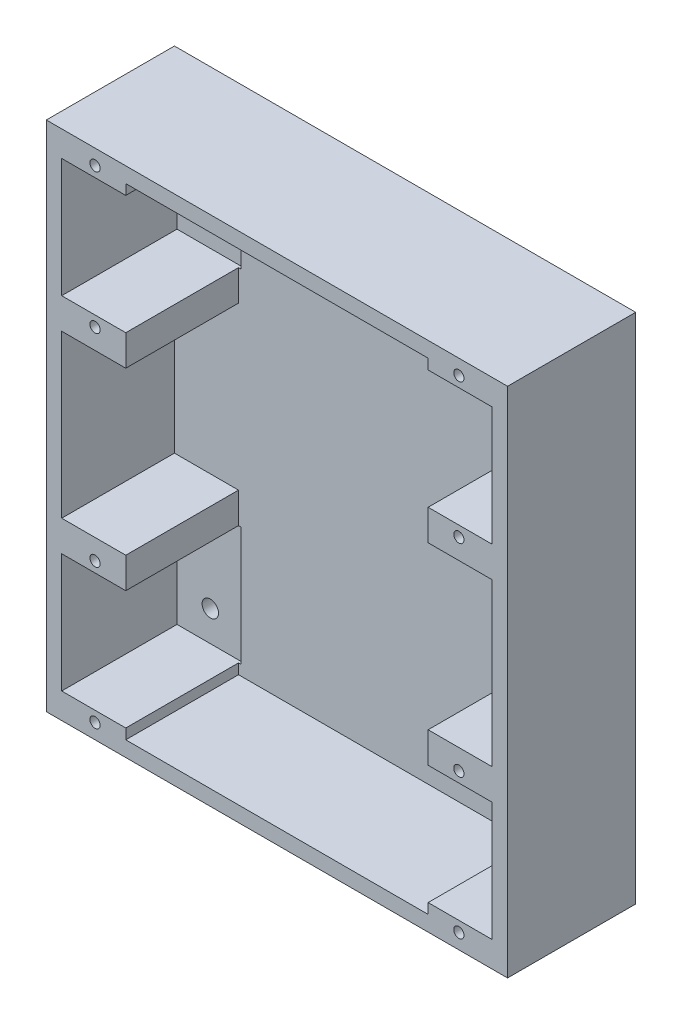
SolidWorks part; units mm, degrees
ref_plane "Plano frontal" through (0, 0, 0) normal (0, 0, 1) x (1, 0, 0)
ref_plane "Plano superior" through (0, 0, 0) normal (0, 1, 0) x (1, 0, 0)
ref_plane "Plano direito" through (0, 0, 0) normal (1, 0, 0) x (0, 0, -1)
sketch "Esboço1" plane through (0, 0, 0) normal (0, 0, 1) x (1, 0, 0)
  line L0 (35.5, 47.05) -> (35.5, 19.75) construction
  line L1 (-45, 50) -> (45, 50)
  line L2 (-45, 50) -> (-45, -50)
  line L3 (-45, -50) -> (45, -50)
  line L4 (45, 50) -> (45, -50)
  line L5 (-45, 50) -> (45, -50) construction
  line L6 (-45, -50) -> (45, 50) construction
  line L7 (29, 45) -> (42, 45)
  line L8 (29, 45) -> (29, 21.8)
  line L9 (29, 21.8) -> (42, 21.8)
  line L10 (42, 45) -> (42, 21.8)
  line L11 (29, 45) -> (42, 21.8) construction
  line L12 (29, 21.8) -> (42, 45) construction
  line L13 (-11.651, 0) -> (14.1427, 0) construction
  line L14 (0, 12.3596) -> (0, -15.2082) construction
  line L15 (29, -21.8) -> (42, -45) construction
  line L16 (29, -45) -> (42, -21.8) construction
  line L17 (35.5, -47.05) -> (35.5, -19.75) construction
  line L18 (42, -45) -> (42, -21.8)
  line L19 (29, -21.8) -> (42, -21.8)
  line L20 (29, -45) -> (29, -21.8)
  line L21 (29, -45) -> (42, -45)
  line L22 (-35.5, -47.05) -> (-35.5, -19.75) construction
  line L23 (-29, -45) -> (-42, -21.8) construction
  line L24 (-29, -21.8) -> (-42, -45) construction
  line L25 (-29, 21.8) -> (-42, 45) construction
  line L26 (-29, 45) -> (-42, 21.8) construction
  line L27 (-35.5, 47.05) -> (-35.5, 19.75) construction
  line L28 (-29, -45) -> (-42, -45)
  line L29 (-29, -45) -> (-29, -21.8)
  line L30 (-29, -21.8) -> (-42, -21.8)
  line L31 (-42, -45) -> (-42, -21.8)
  line L32 (-42, 45) -> (-42, 21.8)
  line L33 (-29, 21.8) -> (-42, 21.8)
  line L34 (-29, 45) -> (-29, 21.8)
  line L35 (-29, 45) -> (-42, 45)
  line L37 (10.2789, -11.1404) -> (10.2789, 35.8596) construction
  line L38 (10.2789, -11.1404) -> (45.2789, -11.1404) construction
  line L39 (45.2789, -11.1404) -> (45.2789, 35.8596) construction
  line L40 (10.2789, 35.8596) -> (45.2789, 35.8596) construction
  line L41 (10.2789, -11.1404) -> (45.2789, 35.8596) construction
  line L42 (45.2789, -11.1404) -> (10.2789, 35.8596) construction
  line L43 (-31.1, -20.1621) -> (31.1, -20.1621) construction
  line L44 (-31.1, -20.1621) -> (-31.1, -42.4621) construction
  line L45 (-31.1, -42.4621) -> (31.1, -42.4621) construction
  line L46 (31.1, -20.1621) -> (31.1, -42.4621) construction
  line L47 (-31.1, -20.1621) -> (31.1, -42.4621) construction
  line L48 (-31.1, -42.4621) -> (31.1, -20.1621) construction
  circle A0 centre (35.5, 19.75) radius 1
  circle A1 centre (35.5, 47.05) radius 1
  circle A2 centre (35.5, 38.5) radius 6.5 construction
  circle A3 centre (35.5, -38.5) radius 6.5 construction
  circle A4 centre (35.5, -47.05) radius 1
  circle A5 centre (35.5, -19.75) radius 1
  circle A6 centre (-35.5, -38.5) radius 6.5 construction
  circle A7 centre (-35.5, 38.5) radius 6.5 construction
  circle A8 centre (-35.5, -19.75) radius 1
  circle A9 centre (-35.5, -47.05) radius 1
  circle A10 centre (-35.5, 47.05) radius 1
  circle A11 centre (-35.5, 19.75) radius 1
  point P0 (0, 0)
  point P6 (35.5, 33.4)
  point P18 (35.5, 33.4)
  point P33 (35.5, -33.4)
  point P54 (-35.5, -33.4)
  point P55 (-35.5, 33.4)
  point P56 (27.7789, 12.3596)
  point P61 (0, -31.3121)
  dimension "D4" = 2
  dimension "D1" = 23.2
  dimension "D2" = 13
  dimension "D3" = 3
  dimension "D5" = 27.3
  dimension "D6" = 5
  dimension "D7" = 47
  dimension "D8" = 35
  dimension "D9" = 62.2
  dimension "D10" = 22.3
  dimension "D11" = 90
  dimension "D12" = 100
extrude "Ressalto-extrusão1" add sketch "Esboço1" along normal blind 25
sketch "Esboço3" plane through (0, 0, 25) normal (0, 0, 1) x (1, 0, 0)
  line L0 (-29, 33.4) -> (-29.5, 33.4) construction
  line L1 (-29.5, 47) -> (29.5, 47)
  line L2 (-29.5, 47) -> (-29.5, 15.8)
  line L3 (-29.5, -47) -> (29.5, -47)
  line L4 (29.5, 47) -> (29.5, 15.8)
  line L5 (-29, 21.8) -> (-29, 45) construction
  line L6 (-29.5, -15.8) -> (-42, -15.8)
  line L7 (29, 45) -> (29, 21.8) construction
  line L9 (0, 50) -> (0, 47) construction
  line L10 (42, -15.8) -> (29.5, -15.8)
  line L11 (42, -15.8) -> (42, 15.8)
  line L12 (45, 50) -> (-45, 50) construction
  line L13 (0, -50) -> (0, -47) construction
  line L14 (-45, -50) -> (45, -50) construction
  line L15 (42, 15.8) -> (29.5, 15.8)
  line L16 (-42, -15.8) -> (-42, 15.8)
  line L17 (42, -15.8) -> (-42, 15.8) construction
  line L18 (42, 15.8) -> (-42, -15.8) construction
  line L19 (29.5, -15.8) -> (29.5, -47)
  line L20 (-29.5, -15.8) -> (-29.5, -47)
  line L21 (-29.5, 15.8) -> (-42, 15.8)
  line L22 (-45, 50) -> (-45, -50) construction
  line L23 (-29, -21.8) -> (-42, -21.8) construction
  point P8 (0, 0)
  dimension "D1" = 0.5
  dimension "D2" = 3
  dimension "D3" = 3
  dimension "D4" = 6
  dimension "D5" = 0.5
extrude "Corte-extrusão1" cut sketch "Esboço3" against normal offset from surface (22 mm away) 3 up to face at (-35.5, -33.4, 0)
sketch "Esboço4" plane through (0, 0, 0) normal (0, 0, -1) x (-1, 0, 0)
  line L0 (-42, -45) -> (-42, -21.8) construction
  line L1 (45, 50) -> (-45, 50)
  line L2 (45, 50) -> (45, -50)
  line L3 (45, -50) -> (-45, -50)
  line L4 (-45, 50) -> (-45, -50)
  line L5 (45, 50) -> (-45, -50) construction
  line L6 (45, -50) -> (-45, 50) construction
  line L7 (-29, -45) -> (-42, -45) construction
  line L9 (-14.847, 0) -> (0, 0) construction
  line L10 (0, -11.1268) -> (0, 0) construction
  circle A0 centre (-35.5, -39.05) radius 1.6
  circle A1 centre (-35.5, 39.05) radius 1.6
  circle A2 centre (35.5, 39.05) radius 1.6
  circle A3 centre (35.5, -39.05) radius 1.6
  point P0 (0, 0)
  point P11 (-42, -33.4)
  point P15 (-35.5, -45)
  dimension "D2" = 3.2
  dimension "D1" = 5.65
extrude "Ressalto-extrusão2" add sketch "Esboço4" against normal blind 2.5
equation "\"D3@Esboço3\"=\"D2@Esboço3\""
